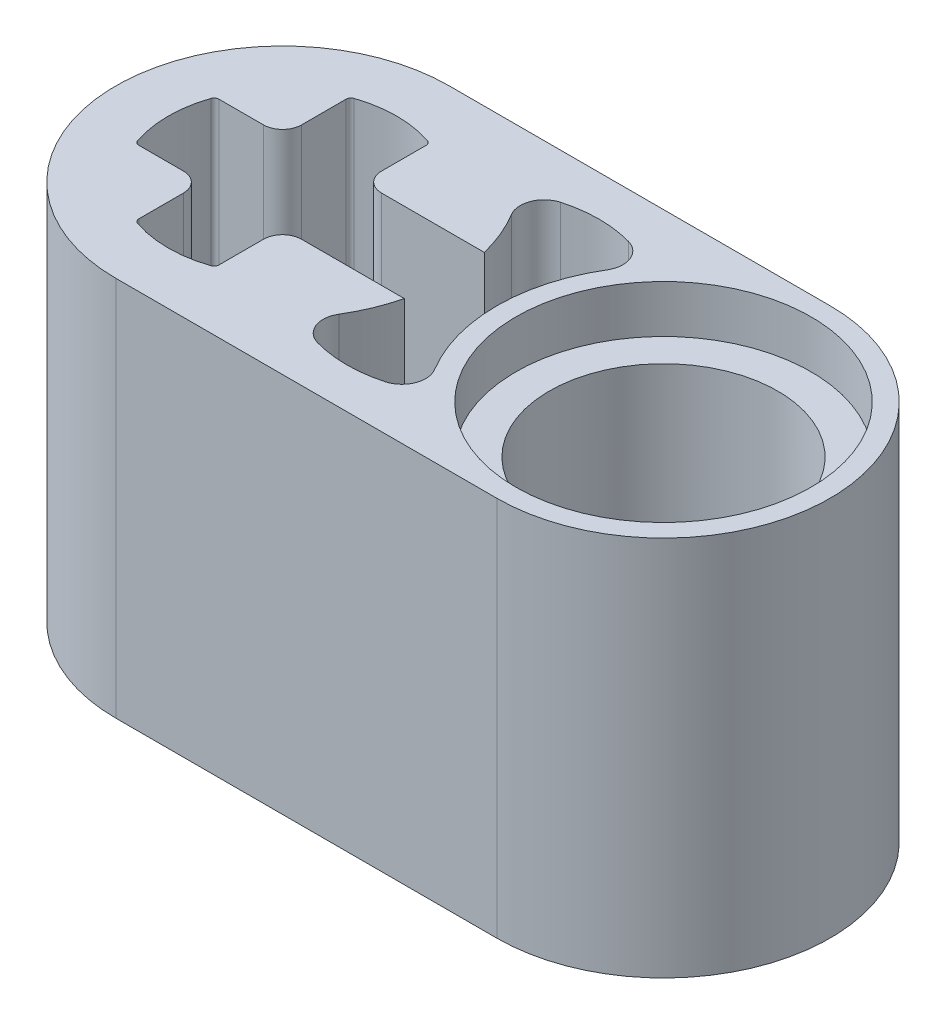
SolidWorks part; units mm, degrees
ref_plane "Front Plane" through (0, 0, 0) normal (0, 0, 1) x (1, 0, 0)
ref_plane "Top Plane" through (0, 0, 0) normal (0, 1, 0) x (1, 0, 0)
ref_plane "Right Plane" through (0, 0, 0) normal (1, 0, 0) x (0, 0, -1)
sketch "Sketch1" plane through (0, 0, 0) normal (0, 1, 0) x (1, 0, 0)
  line L0 (-4, 0) -> (4, 0) construction
  line L1 (-4, 3.5) -> (4, 3.5)
  line L2 (-4, -3.5) -> (4, -3.5)
  arc A0 (-4, 3.5) -> (-4, -3.5) centre (-4, 0) ccw
  arc A1 (4, -3.5) -> (4, 3.5) centre (4, 0) ccw
  point P2 (0, 0)
  dimension "D1" = 8
  dimension "D2" = 3.5
extrude "Boss-Extrude1" add sketch "Sketch1" along normal mid plane 8 contours L1 A1 L2 A0
sketch "Sketch2" plane through (0, 4, 0) normal (0, 1, 0) x (1, 0, 0)
  line L0 (-4.3139, 0.84) -> (-4.84, 0.84) construction
  line L1 (-4.84, -2.2482) -> (-3.16, -2.2482) construction
  line L2 (-4.84, -2.1777) -> (-4.84, -1.24)
  line L3 (-4.84, 2.2482) -> (-3.16, 2.2482) construction
  line L4 (-3.16, -2.1777) -> (-3.16, -1.24)
  line L5 (-4.84, -2.2482) -> (-3.16, 2.2482) construction
  line L6 (-4.84, 2.2482) -> (-3.16, -2.2482) construction
  line L7 (-1.8223, 0.84) -> (-2.76, 0.84)
  line L8 (-1.7518, 0.84) -> (-1.7518, -0.84) construction
  line L9 (-1.8223, -0.84) -> (-2.76, -0.84)
  line L10 (-6.2482, 0.84) -> (-6.2482, -0.84) construction
  line L11 (-1.7518, 0.84) -> (-6.2482, -0.84) construction
  line L12 (-1.7518, -0.84) -> (-6.2482, 0.84) construction
  line L13 (-5.24, 0.84) -> (-6.1777, 0.84)
  line L14 (-3.6861, 0.84) -> (-4.3139, 0.84) construction
  line L15 (-3.16, 0.84) -> (-3.6861, 0.84) construction
  line L16 (-3.16, 0.3139) -> (-3.16, 0.84) construction
  line L17 (-3.16, 1.24) -> (-3.16, 2.1777)
  line L18 (-3.16, -0.3139) -> (-3.16, 0.3139) construction
  line L19 (-3.16, -0.84) -> (-3.16, -0.3139) construction
  line L20 (-3.16, -0.84) -> (-3.6861, -0.84) construction
  line L21 (-5.24, -0.84) -> (-6.1777, -0.84)
  line L22 (-3.6861, -0.84) -> (-4.3139, -0.84) construction
  line L23 (-4.3139, -0.84) -> (-4.84, -0.84) construction
  line L24 (-4.84, -0.84) -> (-4.84, -0.3139) construction
  line L25 (-4.84, 1.24) -> (-4.84, 2.1777)
  line L26 (-4.84, -0.3139) -> (-4.84, 0.3139) construction
  line L27 (-4.84, 0.3139) -> (-4.84, 0.84) construction
  line L28 (-1.8223, 0.84) -> (-0.6023, 0.84)
  line L29 (-1.8223, -0.84) -> (-0.6023, -0.84)
  circle A0 centre (4, 0) radius 2.4
  arc A1 (-4.7722, -2.2724) -> (-3.2278, -2.2724) centre (-4, 0) ccw
  arc A2 (-6.2482, -0.84) -> (-4.84, -2.2482) centre (-4, 0) ccw construction
  arc A3 (-3.16, -2.2482) -> (-1.7518, -0.84) centre (-4, 0) ccw construction
  arc A4 (-1.7276, -0.7722) -> (-1.7276, 0.7722) centre (-4, 0) ccw construction
  arc A5 (-1.7518, 0.84) -> (-3.16, 2.2482) centre (-4, 0) ccw construction
  arc A6 (-3.2278, 2.2724) -> (-4.7722, 2.2724) centre (-4, 0) ccw
  arc A7 (-4.84, 2.2482) -> (-6.2482, 0.84) centre (-4, 0) ccw construction
  arc A8 (-6.2724, 0.7722) -> (-6.2724, -0.7722) centre (-4, 0) ccw
  arc A9 (-6.1777, 0.84) -> (-6.2724, 0.7722) centre (-6.1777, 0.74) ccw
  arc A10 (-6.1777, -0.84) -> (-6.2724, -0.7722) centre (-6.1777, -0.74) cw
  arc A11 (-4.7722, -2.2724) -> (-4.84, -2.1777) centre (-4.74, -2.1777) cw
  arc A12 (-3.2278, -2.2724) -> (-3.16, -2.1777) centre (-3.26, -2.1777) ccw
  arc A13 (-1.7786, -0.83) -> (-1.8223, -0.84) centre (-1.8223, -0.74) cw construction
  arc A14 (-1.7518, 0.8109) -> (-1.7276, 0.7722) centre (-1.8223, 0.74) cw construction
  arc A15 (-3.2278, 2.2724) -> (-3.16, 2.1777) centre (-3.26, 2.1777) cw
  arc A16 (-4.84, 2.1777) -> (-4.7722, 2.2724) centre (-4.74, 2.1777) cw
  arc A17 (-5.24, -0.84) -> (-4.84, -1.24) centre (-5.24, -1.24) cw
  arc A18 (-3.16, -1.24) -> (-2.76, -0.84) centre (-2.76, -1.24) cw
  arc A19 (-2.76, 0.84) -> (-3.16, 1.24) centre (-2.76, 1.24) cw
  arc A20 (-5.24, 0.84) -> (-4.84, 1.24) centre (-5.24, 1.24) ccw
  arc A21 (-0.7122, -2.5525) -> (0.7122, -2.5525) centre (0, 0) ccw
  arc A22 (-1.0056, -1.812) -> (-0.6023, -0.84) centre (-4, 0) ccw
  arc A23 (1.0056, 1.812) -> (1.0056, -1.812) centre (4, 0) ccw
  arc A24 (-1.3466, 2.2824) -> (-1.3466, -2.2824) centre (-4, 0) ccw construction
  arc A25 (-2.1578, -1.5383) -> (-1.3466, -2.2824) centre (0, 0) ccw construction
  arc A26 (-2.467, -0.9677) -> (-2.1578, -1.5383) centre (0, 0) ccw construction
  arc A27 (-2.5977, -0.5239) -> (-2.467, -0.9677) centre (0, 0) ccw construction
  arc A28 (-2.5977, 0.5239) -> (-2.5977, -0.5239) centre (0, 0) ccw construction
  arc A29 (-2.467, 0.9677) -> (-2.5977, 0.5239) centre (0, 0) ccw construction
  arc A30 (-2.1578, 1.5383) -> (-2.467, 0.9677) centre (0, 0) ccw construction
  arc A31 (-1.3466, 2.2824) -> (-2.1578, 1.5383) centre (0, 0) ccw construction
  arc A32 (1.3466, -2.2824) -> (1.3466, 2.2824) centre (4, 0) ccw construction
  arc A33 (2.1578, -1.5383) -> (2.1578, 1.5383) centre (0, 0) ccw construction
  arc A34 (0.7122, 2.5525) -> (-0.7122, 2.5525) centre (0, 0) ccw
  arc A35 (2.1578, 1.5383) -> (1.3466, 2.2824) centre (0, 0) ccw construction
  arc A36 (1.3466, -2.2824) -> (2.1578, -1.5383) centre (0, 0) ccw construction
  arc A37 (-1.0056, -1.812) -> (-0.7122, -2.5525) centre (-0.5778, -2.0709) ccw
  arc A38 (1.0056, -1.812) -> (0.7122, -2.5525) centre (0.5778, -2.0709) cw
  arc A39 (1.0056, 1.812) -> (0.7122, 2.5525) centre (0.5778, 2.0709) ccw
  arc A40 (-1.0056, 1.812) -> (-0.7122, 2.5525) centre (-0.5778, 2.0709) cw
  arc A41 (-1.7276, -0.7722) -> (-1.7518, -0.8109) centre (-1.8223, -0.74) cw construction
  arc A42 (-1.7518, -0.8109) -> (-1.7786, -0.83) centre (-1.8223, -0.74) cw construction
  arc A43 (-1.8223, 0.84) -> (-1.7786, 0.83) centre (-1.8223, 0.74) cw construction
  arc A44 (-1.7786, 0.83) -> (-1.7518, 0.8109) centre (-1.8223, 0.74) cw construction
  arc A45 (-0.6023, -0.84) -> (-0.6023, 0.84) centre (-4, 0) ccw construction
  arc A46 (-0.6023, 0.84) -> (-1.0056, 1.812) centre (-4, 0) ccw
  dimension "D1" = 4.8
  dimension "D2" = 4.8
  dimension "D5" = 0.1
  dimension "D6" = 0.4
  dimension "D7" = 5.3
  dimension "D8" = 7
  dimension "D9" = 7
  dimension "D10" = 0.5
  dimension "D3" = 1.68
  dimension "D4" = 1.68
extrude "Cut-Extrude1" cut sketch "Sketch2" against normal through all
sketch "Sketch3" plane through (0, 4, 0) normal (0, 1, 0) x (1, 0, 0)
  circle A0 centre (4, 0) radius 3.1
  dimension "D1" = 6.2
extrude "Cut-Extrude2" cut sketch "Sketch3" against normal blind 1
mirror "Mirror1" about plane through (0, 0, 0) normal (0, 1, 0) of "Cut-Extrude2"
